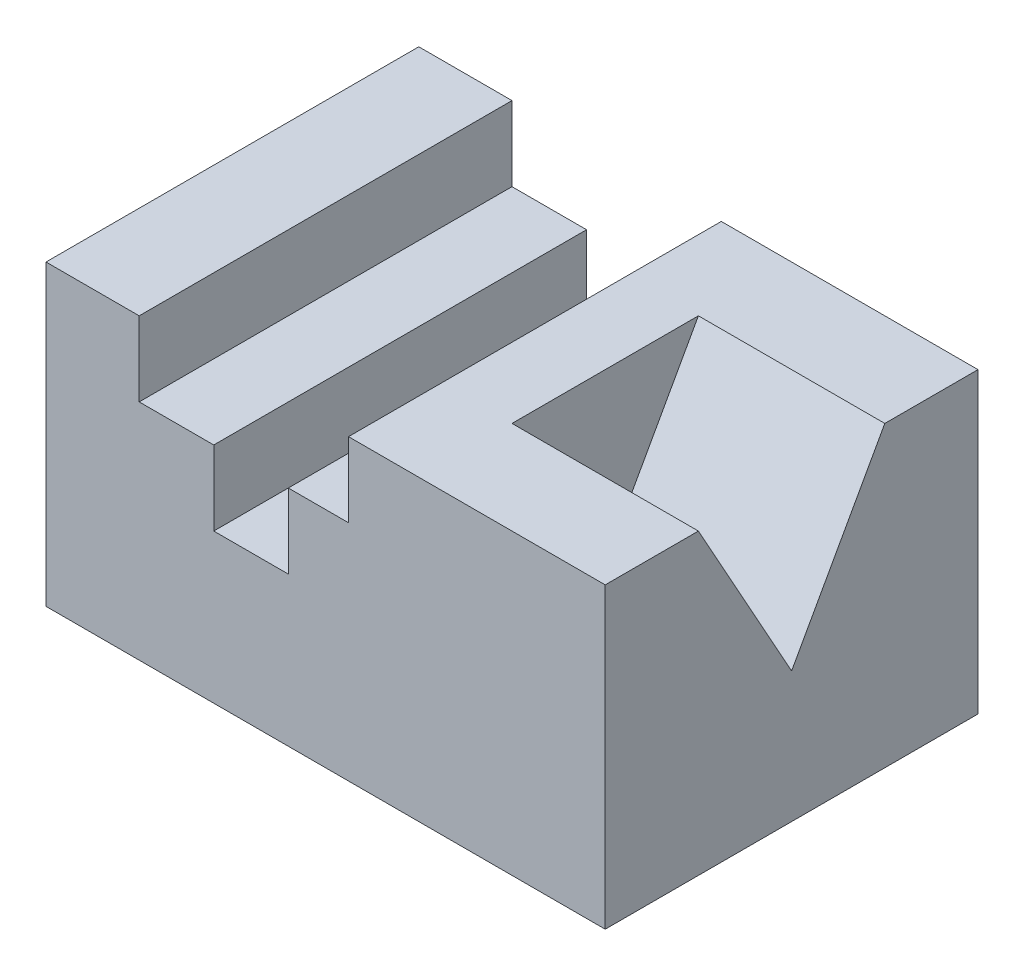
SolidWorks part; units mm, degrees
ref_plane "Front Plane" through (0, 0, 0) normal (0, 0, 1) x (1, 0, 0)
ref_plane "Top Plane" through (0, 0, 0) normal (0, 1, 0) x (1, 0, 0)
ref_plane "Right Plane" through (0, 0, 0) normal (1, 0, 0) x (0, 0, -1)
sketch "Sketch2" plane through (0, 0, 0) normal (0, 0, 1) x (1, 0, 0)
  line L1 (-59.8228, 44.4267) -> (90.1772, 44.4267)
  line L2 (-59.8228, 44.4267) -> (-59.8228, -35.5733)
  line L3 (-59.8228, -35.5733) -> (90.1772, -35.5733)
  line L4 (90.1772, 44.4267) -> (90.1772, -35.5733)
  dimension "D1" = 80
  dimension "D2" = 150
extrude "Boss-Extrude1" add sketch "Sketch2" against normal blind 100
sketch "Sketch3" plane through (0, 0, 0) normal (0, 0, 1) x (1, 0, 0)
  line L0 (-59.8228, 44.4267) -> (-34.8228, 44.4267)
  line L1 (90.1772, 44.4267) -> (-59.8228, 44.4267) construction
  line L2 (-34.8228, 44.4267) -> (-34.8228, 24.4267)
  line L3 (-34.8228, 24.4267) -> (-14.8228, 24.4267)
  line L4 (-14.8228, 24.4267) -> (-14.8228, 4.4267)
  line L5 (-14.8228, 4.4267) -> (5.1772, 4.4267)
  line L6 (5.1772, 4.4267) -> (5.1772, 24.4267)
  line L7 (5.1772, 24.4267) -> (21.3197, 24.4267)
  line L8 (21.3197, 24.4267) -> (21.3197, 44.4267)
  dimension "D1" = 25
  dimension "D2" = 20
  dimension "D3" = 20
  dimension "D4" = 20
  dimension "D5" = 20
  dimension "D6" = 20
extrude "Cut-Extrude1" cut sketch "Sketch3" against normal blind 100 and the other way through all
sketch "Sketch5" plane through (90.1772, 0, 0) normal (1, 0, 0) x (0, 0, -1)
  line L0 (25, 44.4267) -> (50, -0.5733)
  line L1 (100, 44.4267) -> (0, 44.4267) construction
  line L2 (50, -0.5733) -> (75, 44.4267)
  line L3 (0, -35.5733) -> (0, 44.4267) construction
  dimension "D1" = 45
  dimension "D2" = 25
  dimension "D3" = 25
  dimension "D4" = 50
extrude "Cut-Extrude2" cut sketch "Sketch5" against normal blind 50 and the other way through all
